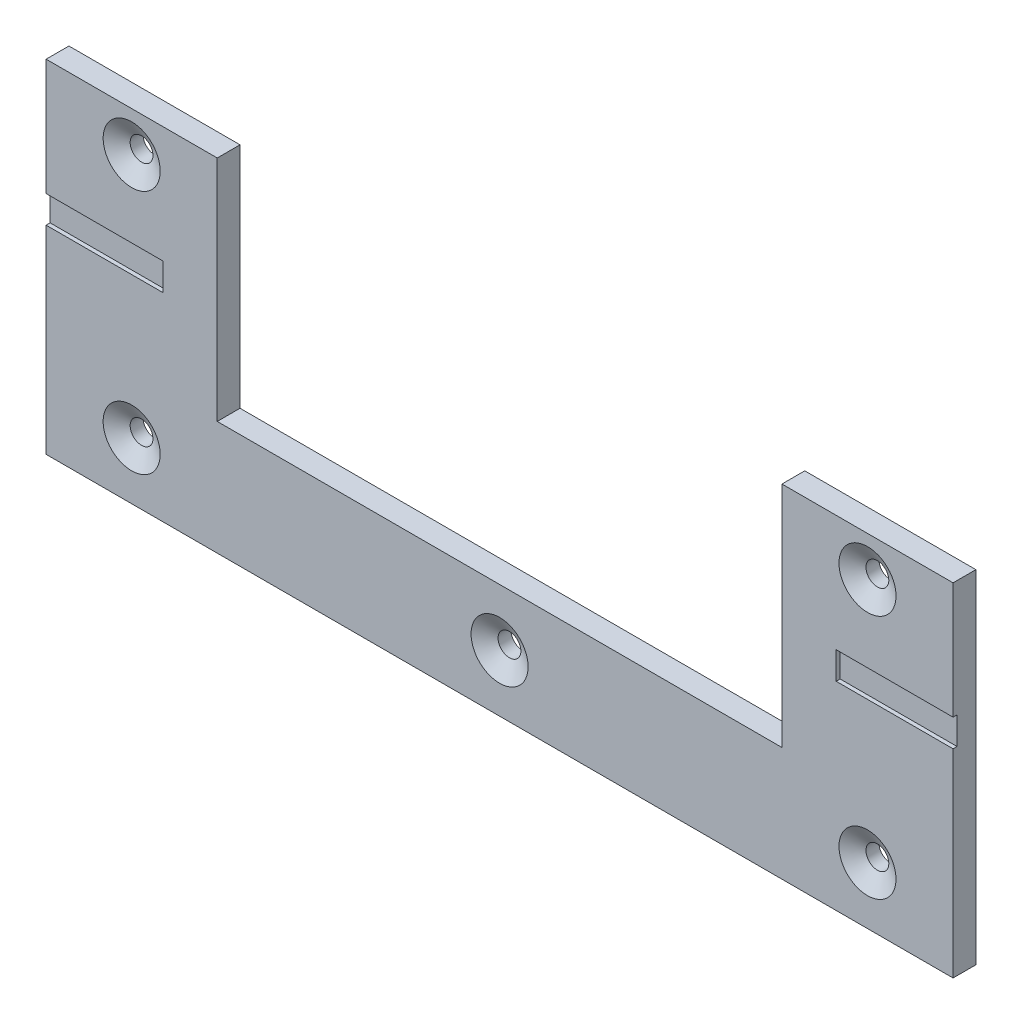
SolidWorks part; units mm, degrees
ref_plane "Plan de face" through (0, 0, 0) normal (0, 0, 1) x (1, 0, 0)
ref_plane "Plan de dessus" through (0, 0, 0) normal (0, 1, 0) x (1, 0, 0)
ref_plane "Plan de droite" through (0, 0, 0) normal (1, 0, 0) x (0, 0, -1)
sketch "Esquisse1" plane through (0, 0, 0) normal (0, 0, 1) x (1, 0, 0)
  line L1 (0, 0) -> (159, 0)
  line L2 (0, 0) -> (0, 60)
  line L3 (0, 60) -> (159, 60)
  line L4 (159, 0) -> (159, 60)
  dimension "D1" = 159
  dimension "D2" = 60
extrude "Boss.-Extru.1" add sketch "Esquisse1" along normal blind 4
sketch "Esquisse2" plane through (0, 0, 0) normal (0, 0, -1) x (-1, 0, 0)
  line L0 (0, 60) -> (0, 0) construction
  line L1 (-20.5, 34.8) -> (0, 34.8)
  line L2 (-20.5, 34.8) -> (-20.5, 39.6)
  line L3 (-20.5, 39.6) -> (0, 39.6)
  line L4 (0, 34.8) -> (0, 39.6)
  line L5 (-159, 60) -> (0, 60) construction
  line L6 (-159, 0) -> (-159, 60) construction
  line L7 (-138.5, 34.8) -> (-159, 34.8)
  line L8 (-138.5, 34.8) -> (-138.5, 39.6)
  line L9 (-138.5, 39.6) -> (-159, 39.6)
  line L10 (-159, 34.8) -> (-159, 39.6)
  dimension "D1" = 20.4
  dimension "D2" = 4.8
  dimension "D3" = 20.5
  dimension "D4" = 4.8
  dimension "D5" = 20.4
  dimension "D6" = 20.5
extrude "Enlèv. mat.-Extru.1" cut sketch "Esquisse2" along normal blind 0.7 from offset 4 offset against normal yes
sketch "Esquisse3" plane through (0, 0, 0) normal (0, 0, -1) x (-1, 0, 0)
  line L0 (-159, 60) -> (0, 60) construction
  line L1 (0, 60) -> (0, 0) construction
  line L2 (-159, 0) -> (-159, 60) construction
  circle A0 centre (-12.5, 31.1873) radius 5.25
  circle A1 centre (-12.5, 43.1873) radius 5.25
  circle A2 centre (-146.5, 31.2047) radius 5.25
  circle A3 centre (-146.5, 43.1873) radius 5.25
  dimension "D3" = 10.5
  dimension "D4" = 10.5
  dimension "D9" = 10.5
  dimension "D10" = 10.5
  dimension "D1" = 28.8127
  dimension "D2" = 12.5
  dimension "D5" = 16.8127
  dimension "D6" = 12.5
  dimension "D7" = 12.5
  dimension "D8" = 12.5
  dimension "D11" = 16.8127
  dimension "D12" = 28.7953
extrude "Enlèv. mat.-Extru.2" cut sketch "Esquisse3" against normal blind 2.3
sketch "Esquisse4" plane through (0, 0, 4) normal (0, 0, 1) x (1, 0, 0)
  line L0 (159, 60) -> (0, 60) construction
  line L1 (30, 60) -> (129, 60)
  line L2 (30, 60) -> (30, 20)
  line L3 (30, 20) -> (129, 20)
  line L4 (129, 60) -> (129, 20)
  line L5 (0, 60) -> (0, 39.6) construction
  line L6 (159, 39.6) -> (159, 60) construction
  line L7 (0, 0) -> (159, 0) construction
  dimension "D1" = 30
  dimension "D2" = 30
  dimension "D3" = 20
extrude "Enlèv. mat.-Extru.3" cut sketch "Esquisse4" against normal blind 4
sketch "Esquisse5" plane through (0, 0, 4) normal (0, 0, 1) x (1, 0, 0)
  line L0 (0, 0) -> (159, 0) construction
  line L1 (0, 34.8) -> (0, 0) construction
  line L2 (159, 0) -> (159, 34.8) construction
  line L3 (159, 60) -> (129, 60) construction
  line L4 (159, 39.6) -> (159, 60) construction
  line L5 (0, 60) -> (0, 39.6) construction
  line L6 (30, 60) -> (0, 60) construction
  circle A0 centre (15, 10) radius 2
  circle A1 centre (144, 10) radius 2
  circle A2 centre (15, 53) radius 2
  circle A3 centre (144, 53) radius 2
  circle A4 centre (79.5, 10) radius 2
  dimension "D1" = 4
  dimension "D2" = 4
  dimension "D7" = 4
  dimension "D8" = 4
  dimension "D13" = 4
  dimension "D3" = 10
  dimension "D4" = 15
  dimension "D5" = 15
  dimension "D6" = 10
  dimension "D9" = 7
  dimension "D10" = 15
  dimension "D11" = 15
  dimension "D12" = 7
  dimension "D14" = 10
  dimension "D15" = 79.5
  dimension "D16" = 79.5
extrude "Enlèv. mat.-Extru.4" cut sketch "Esquisse5" against normal blind 4
chamfer "Chanfrein1" distance 3 angle 30 5 edges at (146, 53, 4) (146, 10, 4) (17, 10, 4) (17, 53, 4) (81.5, 10, 4)
